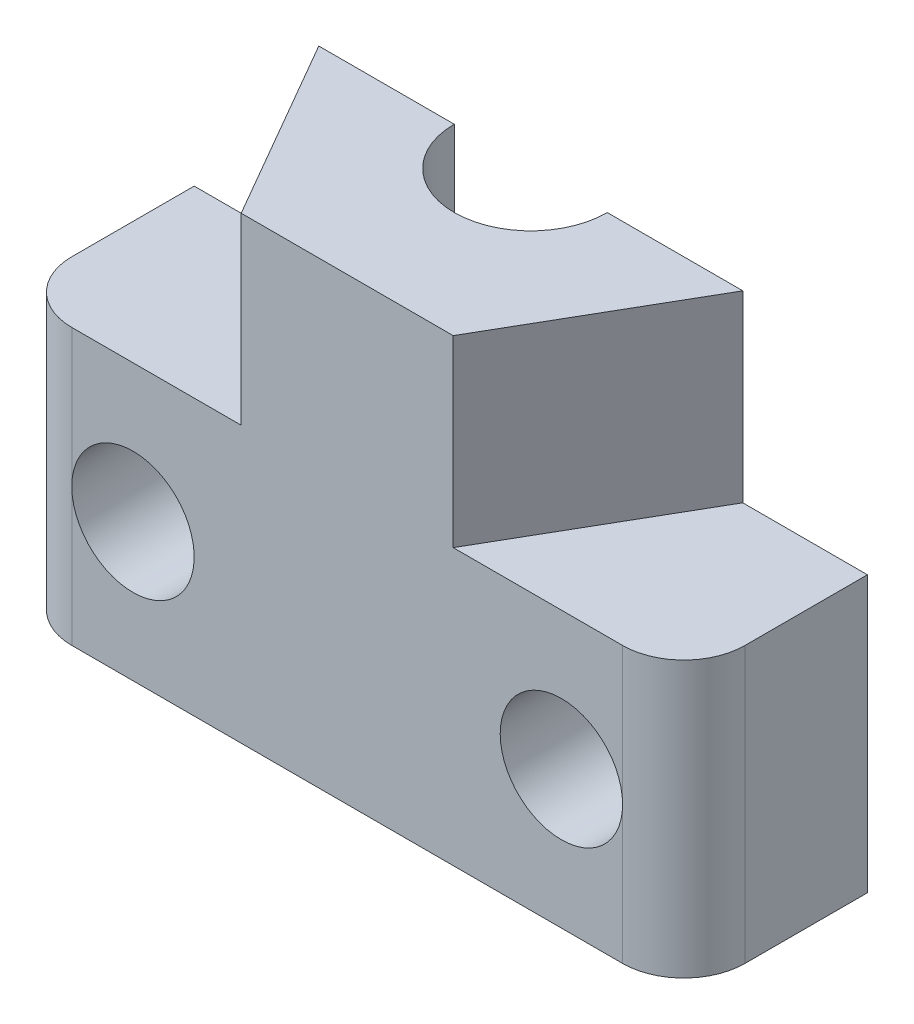
SolidWorks part; units mm, degrees
ref_plane "Спереди" through (0, 0, 0) normal (0, 0, 1) x (1, 0, 0)
ref_plane "Сверху" through (0, 0, 0) normal (0, 1, 0) x (1, 0, 0)
ref_plane "Справа" through (0, 0, 0) normal (1, 0, 0) x (0, 0, -1)
sketch "Эскиз1" plane through (0, 0, 0) normal (0, 1, 0) x (1, 0, 0)
  line L1 (-11, -6) -> (11, -6)
  line L2 (-11, -6) -> (-11, 6)
  line L3 (-11, 6) -> (11, 6)
  line L4 (11, -6) -> (11, 6)
  line L5 (-11, -6) -> (11, 6) construction
  line L6 (-11, 6) -> (11, -6) construction
  point P0 (0, 0)
  dimension "D1" = 12
  dimension "D2" = 22
extrude "Бобышка-Вытянуть1" add sketch "Эскиз1" along normal blind 9
fillet "Скругление1" radius 2 4 edges at (-11, 4.5, -6) (11, 4.5, -6) (11, 4.5, 6) (-11, 4.5, 6)
sketch "Эскиз2" plane through (0, 0, 0) normal (0, 1, 0) x (1, 0, 0)
  circle A0 centre (0, 0) radius 4
  dimension "D1" = 8
extrude "Вырез-Вытянуть1" cut sketch "Эскиз2" along normal blind 8
sketch "Эскиз3" plane through (0, 8, 0) normal (0, -1, 0) x (1, 0, 0)
  circle A0 centre (0, 0) radius 5
  dimension "D1" = 10
extrude "Вырез-Вытянуть2" cut sketch "Эскиз3" against normal blind 1
sketch "Эскиз6" plane through (0, 9, 0) normal (0, 1, 0) x (1, 0, 0)
  line L1 (6.9282, 0) -> (3.4641, 6)
  line L2 (3.4641, 6) -> (-3.4641, 6)
  line L3 (-3.4641, 6) -> (-6.9282, 0)
  line L4 (-6.9282, 0) -> (-3.4641, -6)
  line L5 (-3.4641, -6) -> (3.4641, -6)
  line L6 (3.4641, -6) -> (6.9282, 0)
  circle A0 centre (0, 0) radius 6 construction
extrude "Бобышка-Вытянуть2" add sketch "Эскиз6" along normal blind 6
sketch "Эскиз7" plane through (0, 9, 0) normal (0, 1, 0) x (1, 0, 0)
  line L1 (5.7735, 0) -> (2.8868, 5)
  line L2 (2.8868, 5) -> (-2.8868, 5)
  line L3 (-2.8868, 5) -> (-5.7735, 0)
  line L4 (-5.7735, 0) -> (-2.8868, -5)
  line L5 (-2.8868, -5) -> (2.8868, -5)
  line L6 (2.8868, -5) -> (5.7735, 0)
  circle A0 centre (0, 0) radius 5 construction
extrude "Вырез-Вытянуть5" cut sketch "Эскиз7" along normal blind 3
sketch "Эскиз8" plane through (0, 9, 0) normal (0, 1, 0) x (1, 0, 0)
  circle A0 centre (0, 0) radius 2.5
  dimension "D1" = 5
extrude "Вырез-Вытянуть6" cut sketch "Эскиз8" along normal up to surface (6 mm away) up to face at (0, 15, 0)
sketch "Эскиз11" plane through (0, 0, -6) normal (0, 0, -1) x (-1, 0, 0)
  line L0 (-9, 4.5) -> (9, 4.5) construction
  line L1 (-9, 9) -> (-9, 0) construction
  line L2 (9, 0) -> (9, 9) construction
  circle A0 centre (7, 4.5) radius 2
  dimension "D1" = 7
  dimension "D2" = 4
extrude "Вырез-Вытянуть9" cut sketch "Эскиз11" against normal through all
mirror "Зеркальное отражение6" about plane through (0, 0, 0) normal (1, 0, 0) of "Вырез-Вытянуть9"
sketch "Эскиз12" plane through (0, 0, 0) normal (0, 0, 1) x (1, 0, 0)
  line L1 (-13.5856, -16.6171) -> (13.5856, -16.6171)
  line L2 (-13.5856, -16.6171) -> (-13.5856, 16.6171)
  line L3 (-13.5856, 16.6171) -> (13.5856, 16.6171)
  line L4 (13.5856, -16.6171) -> (13.5856, 16.6171)
  line L5 (-13.5856, -16.6171) -> (13.5856, 16.6171) construction
  line L6 (-13.5856, 16.6171) -> (13.5856, -16.6171) construction
  point P0 (0, 0)
extrude "Вырез-Вытянуть10" cut sketch "Эскиз12" against normal blind 10
